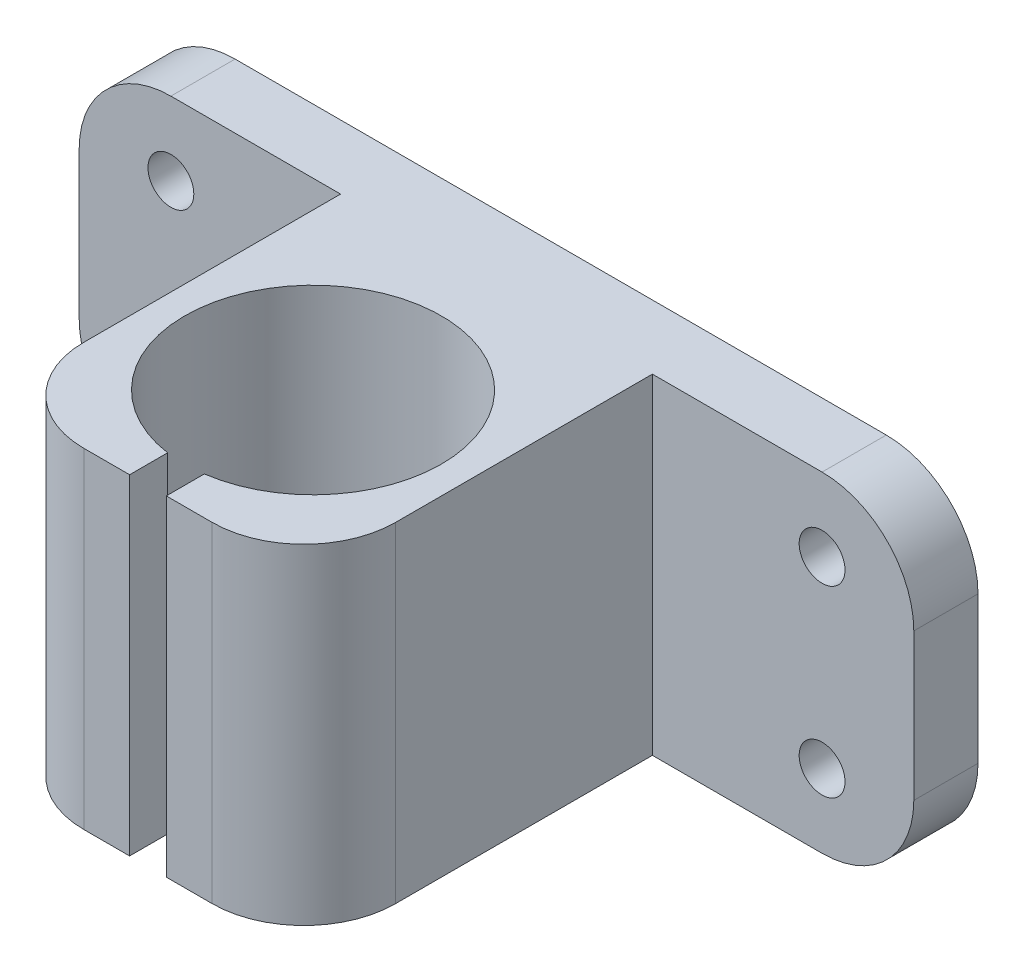
SolidWorks part; units mm, degrees
ref_plane "前基準面" through (0, 0, 0) normal (0, 0, 1) x (1, 0, 0)
ref_plane "上基準面" through (0, 0, 0) normal (0, 1, 0) x (1, 0, 0)
ref_plane "右基準面" through (0, 0, 0) normal (1, 0, 0) x (0, 0, -1)
sketch "草圖1" plane through (0, 0, 0) normal (0, 0, 1) x (1, 0, 0)
  line L0 (0, 0) -> (-19.863, 0) construction
  line L1 (35.5, -18) -> (-35.5, -18)
  line L2 (45.5, -8) -> (45.5, 8)
  line L3 (35.5, 18) -> (-35.5, 18)
  line L4 (-45.5, -8) -> (-45.5, 8)
  line L5 (0, 18) -> (0, -18) construction
  line L6 (45.5, 0) -> (-45.5, 0) construction
  arc A0 (-35.5, 18) -> (-45.5, 8) centre (-35.5, 8) ccw
  arc A1 (35.5, 18) -> (45.5, 8) centre (35.5, 8) cw
  arc A2 (35.5, -18) -> (45.5, -8) centre (35.5, -8) ccw
  arc A3 (-35.5, -18) -> (-45.5, -8) centre (-35.5, -8) cw
  point P0 (0, 0)
  point P6 (-45.5, 18)
  dimension "D3" = 10
  dimension "D1" = 36
  dimension "D2" = 91
extrude "填料-伸長1" add sketch "草圖1" along normal blind 7 contours A0 L4 A3 L1 A2 L2 A1 L3
sketch "草圖2" plane through (0, 0, 7) normal (0, 0, 1) x (1, 0, 0)
  line L1 (35.5, 18) -> (-35.5, 18) construction
  line L2 (0, 18) -> (0, -23.0355) construction
  line L3 (-21.8231, 0) -> (0, 0) construction
  circle A0 centre (-35.5, 10) radius 2.5
  circle A1 centre (35.5, 10) radius 2.5
  circle A2 centre (35.5, -10) radius 2.5
  circle A3 centre (-35.5, -10) radius 2.5
  dimension "D3" = 5
  dimension "D1" = 20
extrude "除料-伸長1" cut sketch "草圖2" against normal blind 10 contours A0 | A1 | A2 | A3
sketch "草圖3" plane through (0, 0, 7) normal (0, 0, 1) x (1, 0, 0)
  line L0 (35.5, 18) -> (-35.5, 18) construction
  line L1 (17, -18) -> (-17, -18)
  line L2 (17, -18) -> (17, 18)
  line L3 (17, 18) -> (-17, 18)
  line L4 (-17, -18) -> (-17, 18)
  line L5 (0, 18) -> (0, -18) construction
  line L6 (17, 0) -> (-17, 0) construction
  point P1 (0, 0)
  dimension "D1" = 34
extrude "填料-伸長2" add sketch "草圖3" along normal blind 38 contours L3 L4 L1 L2
sketch "草圖6" plane through (0, 18, 0) normal (0, 1, 0) x (1, 0, 0)
  line L0 (17, -45) -> (-17, -45) construction
  circle A0 centre (0, -27) radius 14
  dimension "D2" = 28
  dimension "D1" = 18
extrude "除料-伸長2" cut sketch "草圖6" against normal blind 40 contours A0
sketch "草圖8" plane through (0, 0, 45) normal (0, 0, 1) x (1, 0, 0)
  line L0 (17, 18) -> (-17, 18) construction
  line L1 (2, -18) -> (-2, -18)
  line L2 (2, -18) -> (2, 18)
  line L3 (2, 18) -> (-2, 18)
  line L4 (-2, -18) -> (-2, 18)
  line L5 (0, 18) -> (0, -18) construction
  line L6 (2, 0) -> (-2, 0) construction
  point P0 (0, 0)
  dimension "D1" = 4
extrude "除料-伸長3" cut sketch "草圖8" against normal blind 10 contours L2 L1 L4 L3
fillet "圓角1" radius 10 2 edges at (17, 0, 45) (-17, 0, 45)
